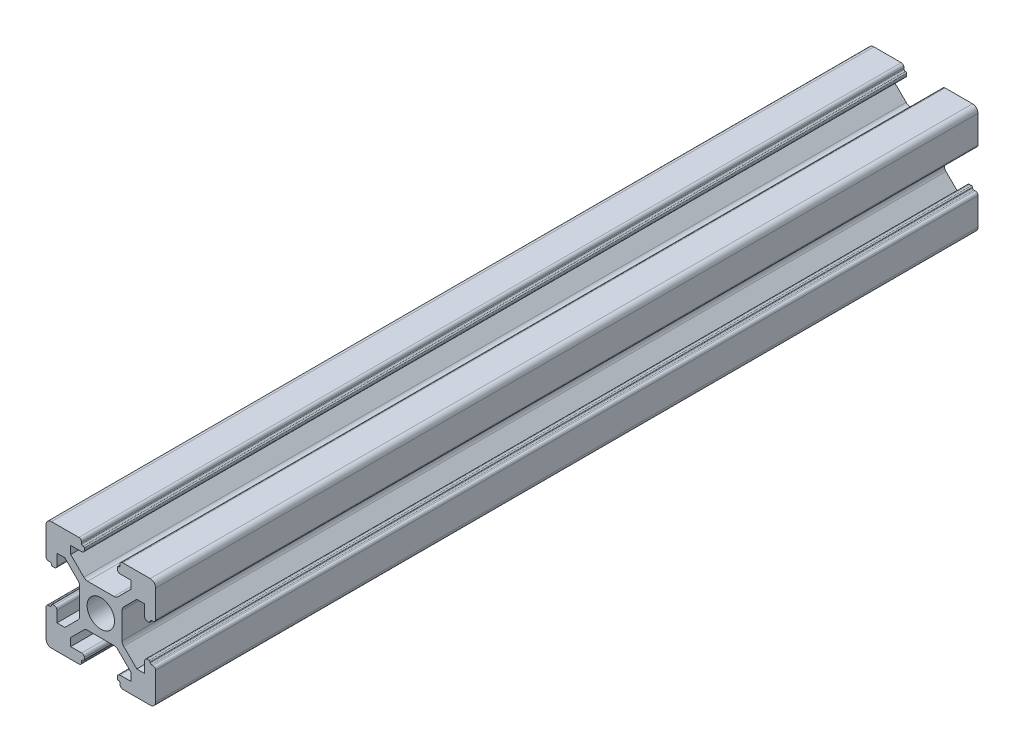
SolidWorks part; units mm, degrees
material "1060 Alloy"
ref_plane "Front Plane" through (0, 0, 0) normal (0, 0, 1) x (1, 0, 0)
ref_plane "Top Plane" through (0, 0, 0) normal (0, 1, 0) x (1, 0, 0)
ref_plane "Right Plane" through (0, 0, 0) normal (1, 0, 0) x (0, 0, -1)
sketch "Sketch2" plane through (0, 0, 0) normal (0, 0, 1) x (1, 0, 0)
  line L0 (3.5, 9.5) -> (3.5, 9.25)
  line L1 (9, -10) -> (-9, -10)
  line L2 (10, -9) -> (10, 9)
  line L3 (9, 10) -> (4, 10)
  line L4 (-10, -9) -> (-10, 9)
  line L5 (10, -10) -> (-10, 10) construction
  line L6 (10, 10) -> (-10, -10) construction
  line L7 (3.25, 9) -> (3.2, 9)
  line L8 (3, 8.8) -> (3, 8.5)
  line L9 (3.5, 8) -> (5.5, 8)
  line L10 (5.5, 8) -> (5.5, 6.5607)
  line L11 (5.5, 6.5607) -> (3.1072, 4.1679)
  line L12 (2.4001, 3.875) -> (0, 3.875)
  line L13 (0, 10) -> (0, 0) construction
  line L14 (0, 10) -> (-9, 10)
  line L15 (10, 10) -> (10, 4)
  line L16 (3.875, 2.4001) -> (3.875, 0)
  line L17 (6.5607, 5.5) -> (4.1679, 3.1072)
  line L18 (8, 5.5) -> (6.5607, 5.5)
  line L19 (8, 3.5) -> (8, 5.5)
  line L20 (8.8, 3) -> (8.5, 3)
  line L21 (9, 3.25) -> (9, 3.2)
  line L22 (9.5, 3.5) -> (9.25, 3.5)
  line L23 (9.5, -3.5) -> (9.25, -3.5)
  line L24 (10, -10) -> (10, -4)
  line L25 (9, -3.25) -> (9, -3.2)
  line L26 (8.8, -3) -> (8.5, -3)
  line L27 (8, -3.5) -> (8, -5.5)
  line L28 (8, -5.5) -> (6.5607, -5.5)
  line L29 (6.5607, -5.5) -> (4.1679, -3.1072)
  line L30 (3.875, -2.4001) -> (3.875, 0)
  line L31 (10, -10) -> (4, -10)
  line L32 (2.4001, -3.875) -> (0, -3.875)
  line L33 (5.5, -6.5607) -> (3.1072, -4.1679)
  line L34 (5.5, -8) -> (5.5, -6.5607)
  line L35 (3.5, -8) -> (5.5, -8)
  line L36 (3, -8.8) -> (3, -8.5)
  line L37 (3.25, -9) -> (3.2, -9)
  line L38 (3.5, -9.5) -> (3.5, -9.25)
  line L39 (10, 0) -> (0, 0) construction
  line L40 (-3.5, -9.5) -> (-3.5, -9.25)
  line L41 (-10, -10) -> (-4, -10)
  line L42 (-3.25, -9) -> (-3.2, -9)
  line L43 (-3, -8.8) -> (-3, -8.5)
  line L44 (-3.5, -8) -> (-5.5, -8)
  line L45 (-5.5, -8) -> (-5.5, -6.5607)
  line L46 (-5.5, -6.5607) -> (-3.1072, -4.1679)
  line L47 (-2.4001, -3.875) -> (0, -3.875)
  line L48 (-10, -10) -> (-10, -4)
  line L49 (-3.875, -2.4001) -> (-3.875, 0)
  line L50 (-6.5607, -5.5) -> (-4.1679, -3.1072)
  line L51 (-8, -5.5) -> (-6.5607, -5.5)
  line L52 (-8, -3.5) -> (-8, -5.5)
  line L53 (-8.8, -3) -> (-8.5, -3)
  line L54 (-9, -3.25) -> (-9, -3.2)
  line L55 (-9.5, -3.5) -> (-9.25, -3.5)
  line L56 (0, -10) -> (0, 0) construction
  line L57 (-9.5, 3.5) -> (-9.25, 3.5)
  line L58 (-10, 10) -> (-10, 4)
  line L59 (-9, 3.25) -> (-9, 3.2)
  line L60 (-8.8, 3) -> (-8.5, 3)
  line L61 (-8, 3.5) -> (-8, 5.5)
  line L62 (-8, 5.5) -> (-6.5607, 5.5)
  line L63 (-6.5607, 5.5) -> (-4.1679, 3.1072)
  line L64 (-3.875, 2.4001) -> (-3.875, 0)
  line L65 (-10, 10) -> (-4, 10)
  line L66 (-2.4001, 3.875) -> (0, 3.875)
  line L67 (-5.5, 6.5607) -> (-3.1072, 4.1679)
  line L68 (-5.5, 8) -> (-5.5, 6.5607)
  line L69 (-3.5, 8) -> (-5.5, 8)
  line L70 (-3, 8.8) -> (-3, 8.5)
  line L71 (-3.25, 9) -> (-3.2, 9)
  line L72 (-3.5, 9.5) -> (-3.5, 9.25)
  line L73 (-10, 0) -> (0, 0) construction
  arc A0 (3.5, 9.5) -> (4, 10) centre (4, 9.5) cw
  arc A1 (3.25, 9) -> (3.5, 9.25) centre (3.25, 9.25) ccw
  arc A2 (3.2, 9) -> (3, 8.8) centre (3.2, 8.8) ccw
  arc A3 (3.5, 8) -> (3, 8.5) centre (3.5, 8.5) cw
  arc A4 (3.1072, 4.1679) -> (2.4001, 3.875) centre (2.4001, 4.875) cw
  arc A5 (4.1679, 3.1072) -> (3.875, 2.4001) centre (4.875, 2.4001) ccw
  arc A6 (8, 3.5) -> (8.5, 3) centre (8.5, 3.5) ccw
  arc A7 (9, 3.2) -> (8.8, 3) centre (8.8, 3.2) cw
  arc A8 (9, 3.25) -> (9.25, 3.5) centre (9.25, 3.25) cw
  arc A9 (9.5, 3.5) -> (10, 4) centre (9.5, 4) ccw
  arc A10 (9.5, -3.5) -> (10, -4) centre (9.5, -4) cw
  arc A11 (9, -3.25) -> (9.25, -3.5) centre (9.25, -3.25) ccw
  arc A12 (9, -3.2) -> (8.8, -3) centre (8.8, -3.2) ccw
  arc A13 (8, -3.5) -> (8.5, -3) centre (8.5, -3.5) cw
  arc A14 (4.1679, -3.1072) -> (3.875, -2.4001) centre (4.875, -2.4001) cw
  arc A15 (3.1072, -4.1679) -> (2.4001, -3.875) centre (2.4001, -4.875) ccw
  arc A16 (3.5, -8) -> (3, -8.5) centre (3.5, -8.5) ccw
  arc A17 (3.2, -9) -> (3, -8.8) centre (3.2, -8.8) cw
  arc A18 (3.25, -9) -> (3.5, -9.25) centre (3.25, -9.25) cw
  arc A19 (3.5, -9.5) -> (4, -10) centre (4, -9.5) ccw
  arc A20 (-3.5, -9.5) -> (-4, -10) centre (-4, -9.5) cw
  arc A21 (-3.25, -9) -> (-3.5, -9.25) centre (-3.25, -9.25) ccw
  arc A22 (-3.2, -9) -> (-3, -8.8) centre (-3.2, -8.8) ccw
  arc A23 (-3.5, -8) -> (-3, -8.5) centre (-3.5, -8.5) cw
  arc A24 (-3.1072, -4.1679) -> (-2.4001, -3.875) centre (-2.4001, -4.875) cw
  arc A25 (-4.1679, -3.1072) -> (-3.875, -2.4001) centre (-4.875, -2.4001) ccw
  arc A26 (-8, -3.5) -> (-8.5, -3) centre (-8.5, -3.5) ccw
  arc A27 (-9, -3.2) -> (-8.8, -3) centre (-8.8, -3.2) cw
  arc A28 (-9, -3.25) -> (-9.25, -3.5) centre (-9.25, -3.25) cw
  arc A29 (-9.5, -3.5) -> (-10, -4) centre (-9.5, -4) ccw
  arc A30 (-9.5, 3.5) -> (-10, 4) centre (-9.5, 4) cw
  arc A31 (-9, 3.25) -> (-9.25, 3.5) centre (-9.25, 3.25) ccw
  arc A32 (-9, 3.2) -> (-8.8, 3) centre (-8.8, 3.2) ccw
  arc A33 (-8, 3.5) -> (-8.5, 3) centre (-8.5, 3.5) cw
  arc A34 (-4.1679, 3.1072) -> (-3.875, 2.4001) centre (-4.875, 2.4001) cw
  arc A35 (-3.1072, 4.1679) -> (-2.4001, 3.875) centre (-2.4001, 4.875) ccw
  arc A36 (-3.5, 8) -> (-3, 8.5) centre (-3.5, 8.5) ccw
  arc A37 (-3.2, 9) -> (-3, 8.8) centre (-3.2, 8.8) cw
  arc A38 (-3.25, 9) -> (-3.5, 9.25) centre (-3.25, 9.25) cw
  arc A39 (-3.5, 9.5) -> (-4, 10) centre (-4, 9.5) ccw
  circle A40 centre (0, 0) radius 2.5
  arc A41 (-10, 9) -> (-9, 10) centre (-9, 9) cw
  arc A42 (-10, -9) -> (-9, -10) centre (-9, -9) ccw
  arc A43 (9, -10) -> (10, -9) centre (9, -9) ccw
  arc A44 (10, 9) -> (9, 10) centre (9, 9) ccw
  point P0 (0, 0)
  point P17 (0, 0)
  point P23 (3.5, 10)
  point P26 (3.5, 9)
  point P52 (9, 3.5)
  point P53 (10, 3.5)
  point P90 (3.5, -9)
  point P91 (3.5, -10)
  point P92 (0, 0)
  point P131 (-9, -3.5)
  point P132 (-10, -3.5)
  point P133 (0, 0)
  point P172 (-3.5, 9)
  point P173 (-3.5, 10)
  point P174 (0, 0)
  dimension "D10" = 0.5
  dimension "D11" = 0.25
  dimension "D12" = 0.2
  dimension "D13" = 0.5
  dimension "D14" = 1
  dimension "D16" = 5
  dimension "D17" = 1
  dimension "D1" = 20
  dimension "D2" = 20
  dimension "D3" = 1.5
  dimension "D4" = 3.875
  dimension "D5" = 11
  dimension "D6" = 7
  dimension "D7" = 6
  dimension "D8" = 2
  dimension "D9" = 1
  dimension "D15" = 4
extrude "Boss-Extrude1" add sketch "Sketch2" along normal blind 150 contours L72 A39 L14 L4 A30 L57 A31 L59 A32 L60 A33 L61 L62 L63 A34 L64 L49 A25 L50 L51 L52 A26 L53 A27 L54 A28 L55 A29 L1 A20 L40 A21 L42 A22 L43 A23 L44 L45 L46 A24 L47 L32 A15 L33 L34 L35 A16 L36 A17 L37
sketch "Sketch3" plane through (0, 0, 150) normal (0, 0, 1) x (1, 0, 0)
  line L60 (10, 4) -> (10, 9)
  line L61 (9, 10) -> (4, 10)
  line L62 (3.5, 9.5) -> (3.5, 9.25)
  line L63 (3.25, 9) -> (3.2, 9)
  line L64 (3, 8.8) -> (3, 8.5)
  line L65 (3.5, 8) -> (5.5, 8)
  line L66 (5.5, 8) -> (5.5, 6.5607)
  line L67 (5.5, 6.5607) -> (3.1072, 4.1679)
  line L68 (2.4001, 3.875) -> (-2.4001, 3.875)
  line L69 (-3.1072, 4.1679) -> (-5.5, 6.5607)
  line L70 (-5.5, 6.5607) -> (-5.5, 8)
  line L71 (-5.5, 8) -> (-3.5, 8)
  line L72 (-3, 8.5) -> (-3, 8.8)
  line L73 (-3.2, 9) -> (-3.25, 9)
  line L74 (-3.5, 9.25) -> (-3.5, 9.5)
  line L75 (-4, 10) -> (-9, 10)
  line L76 (-10, 9) -> (-10, 4)
  line L77 (-9.5, 3.5) -> (-9.25, 3.5)
  line L78 (-9, 3.25) -> (-9, 3.2)
  line L79 (-8.8, 3) -> (-8.5, 3)
  line L80 (-8, 3.5) -> (-8, 5.5)
  line L81 (-8, 5.5) -> (-6.5607, 5.5)
  line L82 (-6.5607, 5.5) -> (-4.1679, 3.1072)
  line L83 (-3.875, 2.4001) -> (-3.875, -2.4001)
  line L84 (-4.1679, -3.1072) -> (-6.5607, -5.5)
  line L85 (-6.5607, -5.5) -> (-8, -5.5)
  line L86 (-8, -5.5) -> (-8, -3.5)
  line L87 (-8.5, -3) -> (-8.8, -3)
  line L88 (-9, -3.2) -> (-9, -3.25)
  line L89 (-9.25, -3.5) -> (-9.5, -3.5)
  line L90 (-10, -4) -> (-10, -9)
  line L91 (-9, -10) -> (-4, -10)
  line L92 (-3.5, -9.5) -> (-3.5, -9.25)
  line L93 (-3.25, -9) -> (-3.2, -9)
  line L94 (-3, -8.8) -> (-3, -8.5)
  line L95 (-3.5, -8) -> (-5.5, -8)
  line L96 (-5.5, -8) -> (-5.5, -6.5607)
  line L97 (-5.5, -6.5607) -> (-3.1072, -4.1679)
  line L98 (-2.4001, -3.875) -> (2.4001, -3.875)
  line L99 (3.1072, -4.1679) -> (5.5, -6.5607)
  line L100 (5.5, -6.5607) -> (5.5, -8)
  line L101 (5.5, -8) -> (3.5, -8)
  line L102 (3, -8.5) -> (3, -8.8)
  line L103 (3.2, -9) -> (3.25, -9)
  line L104 (3.5, -9.25) -> (3.5, -9.5)
  line L105 (4, -10) -> (9, -10)
  line L106 (10, -9) -> (10, -4)
  line L107 (9.5, -3.5) -> (9.25, -3.5)
  line L108 (9, -3.25) -> (9, -3.2)
  line L109 (8.8, -3) -> (8.5, -3)
  line L110 (8, -3.5) -> (8, -5.5)
  line L111 (8, -5.5) -> (6.5607, -5.5)
  line L112 (6.5607, -5.5) -> (4.1679, -3.1072)
  line L113 (3.875, -2.4001) -> (3.875, 2.4001)
  line L114 (4.1679, 3.1072) -> (6.5607, 5.5)
  line L115 (6.5607, 5.5) -> (8, 5.5)
  line L116 (8, 5.5) -> (8, 3.5)
  line L117 (8.5, 3) -> (8.8, 3)
  line L118 (9, 3.2) -> (9, 3.25)
  line L119 (9.25, 3.5) -> (9.5, 3.5)
  line L120 (10, 4) -> (10, 9)
  line L121 (9, 10) -> (4, 10)
  line L122 (3.5, 9.5) -> (3.5, 9.25)
  line L123 (3.25, 9) -> (3.2, 9)
  line L124 (3, 8.8) -> (3, 8.5)
  line L125 (3.5, 8) -> (5.5, 8)
  line L126 (5.5, 8) -> (5.5, 6.5607)
  line L127 (5.5, 6.5607) -> (3.1072, 4.1679)
  line L128 (2.4001, 3.875) -> (-2.4001, 3.875)
  line L129 (-3.1072, 4.1679) -> (-5.5, 6.5607)
  line L130 (-5.5, 6.5607) -> (-5.5, 8)
  line L131 (-5.5, 8) -> (-3.5, 8)
  line L132 (-3, 8.5) -> (-3, 8.8)
  line L133 (-3.2, 9) -> (-3.25, 9)
  line L134 (-3.5, 9.25) -> (-3.5, 9.5)
  line L135 (-4, 10) -> (-9, 10)
  line L136 (-10, 9) -> (-10, 4)
  line L137 (-9.5, 3.5) -> (-9.25, 3.5)
  line L138 (-9, 3.25) -> (-9, 3.2)
  line L139 (-8.8, 3) -> (-8.5, 3)
  line L140 (-8, 3.5) -> (-8, 5.5)
  line L141 (-8, 5.5) -> (-6.5607, 5.5)
  line L142 (-6.5607, 5.5) -> (-4.1679, 3.1072)
  line L143 (-3.875, 2.4001) -> (-3.875, -2.4001)
  line L144 (-4.1679, -3.1072) -> (-6.5607, -5.5)
  line L145 (-6.5607, -5.5) -> (-8, -5.5)
  line L146 (-8, -5.5) -> (-8, -3.5)
  line L147 (-8.5, -3) -> (-8.8, -3)
  line L148 (-9, -3.2) -> (-9, -3.25)
  line L149 (-9.25, -3.5) -> (-9.5, -3.5)
  line L150 (-10, -4) -> (-10, -9)
  line L151 (-9, -10) -> (-4, -10)
  line L152 (-3.5, -9.5) -> (-3.5, -9.25)
  line L153 (-3.25, -9) -> (-3.2, -9)
  line L154 (-3, -8.8) -> (-3, -8.5)
  line L155 (-3.5, -8) -> (-5.5, -8)
  line L156 (-5.5, -8) -> (-5.5, -6.5607)
  line L157 (-5.5, -6.5607) -> (-3.1072, -4.1679)
  line L158 (-2.4001, -3.875) -> (2.4001, -3.875)
  line L159 (3.1072, -4.1679) -> (5.5, -6.5607)
  line L160 (5.5, -6.5607) -> (5.5, -8)
  line L161 (5.5, -8) -> (3.5, -8)
  line L162 (3, -8.5) -> (3, -8.8)
  line L163 (3.2, -9) -> (3.25, -9)
  line L164 (3.5, -9.25) -> (3.5, -9.5)
  line L165 (4, -10) -> (9, -10)
  line L166 (10, -9) -> (10, -4)
  line L167 (9.5, -3.5) -> (9.25, -3.5)
  line L168 (9, -3.25) -> (9, -3.2)
  line L169 (8.8, -3) -> (8.5, -3)
  line L170 (8, -3.5) -> (8, -5.5)
  line L171 (8, -5.5) -> (6.5607, -5.5)
  line L172 (6.5607, -5.5) -> (4.1679, -3.1072)
  line L173 (3.875, -2.4001) -> (3.875, 2.4001)
  line L174 (4.1679, 3.1072) -> (6.5607, 5.5)
  line L175 (6.5607, 5.5) -> (8, 5.5)
  line L176 (8, 5.5) -> (8, 3.5)
  line L177 (8.5, 3) -> (8.8, 3)
  line L178 (9, 3.2) -> (9, 3.25)
  line L179 (9.25, 3.5) -> (9.5, 3.5)
  arc A44 (10, 9) -> (9, 10) centre (9, 9) ccw
  arc A45 (4, 10) -> (3.5, 9.5) centre (4, 9.5) ccw
  arc A46 (3.25, 9) -> (3.5, 9.25) centre (3.25, 9.25) ccw
  arc A47 (3.2, 9) -> (3, 8.8) centre (3.2, 8.8) ccw
  arc A48 (3, 8.5) -> (3.5, 8) centre (3.5, 8.5) ccw
  arc A49 (2.4001, 3.875) -> (3.1072, 4.1679) centre (2.4001, 4.875) ccw
  arc A50 (-3.1072, 4.1679) -> (-2.4001, 3.875) centre (-2.4001, 4.875) ccw
  arc A51 (-3.5, 8) -> (-3, 8.5) centre (-3.5, 8.5) ccw
  arc A52 (-3, 8.8) -> (-3.2, 9) centre (-3.2, 8.8) ccw
  arc A53 (-3.5, 9.25) -> (-3.25, 9) centre (-3.25, 9.25) ccw
  arc A54 (-3.5, 9.5) -> (-4, 10) centre (-4, 9.5) ccw
  arc A55 (-9, 10) -> (-10, 9) centre (-9, 9) ccw
  arc A56 (-10, 4) -> (-9.5, 3.5) centre (-9.5, 4) ccw
  arc A57 (-9, 3.25) -> (-9.25, 3.5) centre (-9.25, 3.25) ccw
  arc A58 (-9, 3.2) -> (-8.8, 3) centre (-8.8, 3.2) ccw
  arc A59 (-8.5, 3) -> (-8, 3.5) centre (-8.5, 3.5) ccw
  arc A60 (-3.875, 2.4001) -> (-4.1679, 3.1072) centre (-4.875, 2.4001) ccw
  arc A61 (-4.1679, -3.1072) -> (-3.875, -2.4001) centre (-4.875, -2.4001) ccw
  arc A62 (-8, -3.5) -> (-8.5, -3) centre (-8.5, -3.5) ccw
  arc A63 (-8.8, -3) -> (-9, -3.2) centre (-8.8, -3.2) ccw
  arc A64 (-9.25, -3.5) -> (-9, -3.25) centre (-9.25, -3.25) ccw
  arc A65 (-9.5, -3.5) -> (-10, -4) centre (-9.5, -4) ccw
  arc A66 (-10, -9) -> (-9, -10) centre (-9, -9) ccw
  arc A67 (-4, -10) -> (-3.5, -9.5) centre (-4, -9.5) ccw
  arc A68 (-3.25, -9) -> (-3.5, -9.25) centre (-3.25, -9.25) ccw
  arc A69 (-3.2, -9) -> (-3, -8.8) centre (-3.2, -8.8) ccw
  arc A70 (-3, -8.5) -> (-3.5, -8) centre (-3.5, -8.5) ccw
  arc A71 (-2.4001, -3.875) -> (-3.1072, -4.1679) centre (-2.4001, -4.875) ccw
  arc A72 (3.1072, -4.1679) -> (2.4001, -3.875) centre (2.4001, -4.875) ccw
  arc A73 (3.5, -8) -> (3, -8.5) centre (3.5, -8.5) ccw
  arc A74 (3, -8.8) -> (3.2, -9) centre (3.2, -8.8) ccw
  arc A75 (3.5, -9.25) -> (3.25, -9) centre (3.25, -9.25) ccw
  arc A76 (3.5, -9.5) -> (4, -10) centre (4, -9.5) ccw
  arc A77 (9, -10) -> (10, -9) centre (9, -9) ccw
  arc A78 (10, -4) -> (9.5, -3.5) centre (9.5, -4) ccw
  arc A79 (9, -3.25) -> (9.25, -3.5) centre (9.25, -3.25) ccw
  arc A80 (9, -3.2) -> (8.8, -3) centre (8.8, -3.2) ccw
  arc A81 (8.5, -3) -> (8, -3.5) centre (8.5, -3.5) ccw
  arc A82 (3.875, -2.4001) -> (4.1679, -3.1072) centre (4.875, -2.4001) ccw
  arc A83 (4.1679, 3.1072) -> (3.875, 2.4001) centre (4.875, 2.4001) ccw
  arc A84 (8, 3.5) -> (8.5, 3) centre (8.5, 3.5) ccw
  arc A85 (8.8, 3) -> (9, 3.2) centre (8.8, 3.2) ccw
  arc A86 (9.25, 3.5) -> (9, 3.25) centre (9.25, 3.25) ccw
  arc A87 (9.5, 3.5) -> (10, 4) centre (9.5, 4) ccw
  arc A88 (10, 9) -> (9, 10) centre (9, 9) ccw
  arc A89 (4, 10) -> (3.5, 9.5) centre (4, 9.5) ccw
  arc A90 (3.25, 9) -> (3.5, 9.25) centre (3.25, 9.25) ccw
  arc A91 (3.2, 9) -> (3, 8.8) centre (3.2, 8.8) ccw
  arc A92 (3, 8.5) -> (3.5, 8) centre (3.5, 8.5) ccw
  arc A93 (2.4001, 3.875) -> (3.1072, 4.1679) centre (2.4001, 4.875) ccw
  arc A94 (-3.1072, 4.1679) -> (-2.4001, 3.875) centre (-2.4001, 4.875) ccw
  arc A95 (-3.5, 8) -> (-3, 8.5) centre (-3.5, 8.5) ccw
  arc A96 (-3, 8.8) -> (-3.2, 9) centre (-3.2, 8.8) ccw
  arc A97 (-3.5, 9.25) -> (-3.25, 9) centre (-3.25, 9.25) ccw
  arc A98 (-3.5, 9.5) -> (-4, 10) centre (-4, 9.5) ccw
  arc A99 (-9, 10) -> (-10, 9) centre (-9, 9) ccw
  arc A100 (-10, 4) -> (-9.5, 3.5) centre (-9.5, 4) ccw
  arc A101 (-9, 3.25) -> (-9.25, 3.5) centre (-9.25, 3.25) ccw
  arc A102 (-9, 3.2) -> (-8.8, 3) centre (-8.8, 3.2) ccw
  arc A103 (-8.5, 3) -> (-8, 3.5) centre (-8.5, 3.5) ccw
  arc A104 (-3.875, 2.4001) -> (-4.1679, 3.1072) centre (-4.875, 2.4001) ccw
  arc A105 (-4.1679, -3.1072) -> (-3.875, -2.4001) centre (-4.875, -2.4001) ccw
  arc A106 (-8, -3.5) -> (-8.5, -3) centre (-8.5, -3.5) ccw
  arc A107 (-8.8, -3) -> (-9, -3.2) centre (-8.8, -3.2) ccw
  arc A108 (-9.25, -3.5) -> (-9, -3.25) centre (-9.25, -3.25) ccw
  arc A109 (-9.5, -3.5) -> (-10, -4) centre (-9.5, -4) ccw
  arc A110 (-10, -9) -> (-9, -10) centre (-9, -9) ccw
  arc A111 (-4, -10) -> (-3.5, -9.5) centre (-4, -9.5) ccw
  arc A112 (-3.25, -9) -> (-3.5, -9.25) centre (-3.25, -9.25) ccw
  arc A113 (-3.2, -9) -> (-3, -8.8) centre (-3.2, -8.8) ccw
  arc A114 (-3, -8.5) -> (-3.5, -8) centre (-3.5, -8.5) ccw
  arc A115 (-2.4001, -3.875) -> (-3.1072, -4.1679) centre (-2.4001, -4.875) ccw
  arc A116 (3.1072, -4.1679) -> (2.4001, -3.875) centre (2.4001, -4.875) ccw
  arc A117 (3.5, -8) -> (3, -8.5) centre (3.5, -8.5) ccw
  arc A118 (3, -8.8) -> (3.2, -9) centre (3.2, -8.8) ccw
  arc A119 (3.5, -9.25) -> (3.25, -9) centre (3.25, -9.25) ccw
  arc A120 (3.5, -9.5) -> (4, -10) centre (4, -9.5) ccw
  arc A121 (9, -10) -> (10, -9) centre (9, -9) ccw
  arc A122 (10, -4) -> (9.5, -3.5) centre (9.5, -4) ccw
  arc A123 (9, -3.25) -> (9.25, -3.5) centre (9.25, -3.25) ccw
  arc A124 (9, -3.2) -> (8.8, -3) centre (8.8, -3.2) ccw
  arc A125 (8.5, -3) -> (8, -3.5) centre (8.5, -3.5) ccw
  arc A126 (3.875, -2.4001) -> (4.1679, -3.1072) centre (4.875, -2.4001) ccw
  arc A127 (4.1679, 3.1072) -> (3.875, 2.4001) centre (4.875, 2.4001) ccw
  arc A128 (8, 3.5) -> (8.5, 3) centre (8.5, 3.5) ccw
  arc A129 (8.8, 3) -> (9, 3.2) centre (8.8, 3.2) ccw
  arc A130 (9.25, 3.5) -> (9, 3.25) centre (9.25, 3.25) ccw
  arc A131 (9.5, 3.5) -> (10, 4) centre (9.5, 4) ccw
  dimension "D1" = 0
ref_plane "Plane1" through (0, 0, 75) normal (0, 0, -1) x (-1, 0, 0)
sketch "Sketch4" plane through (0, 0, 150) normal (0, 0, 1) x (1, 0, 0)
  point P0 (0, 0)
equation "\"Length@Boss-Extrude1\"=150.00mm"
equation "\"Length\"= 150"
